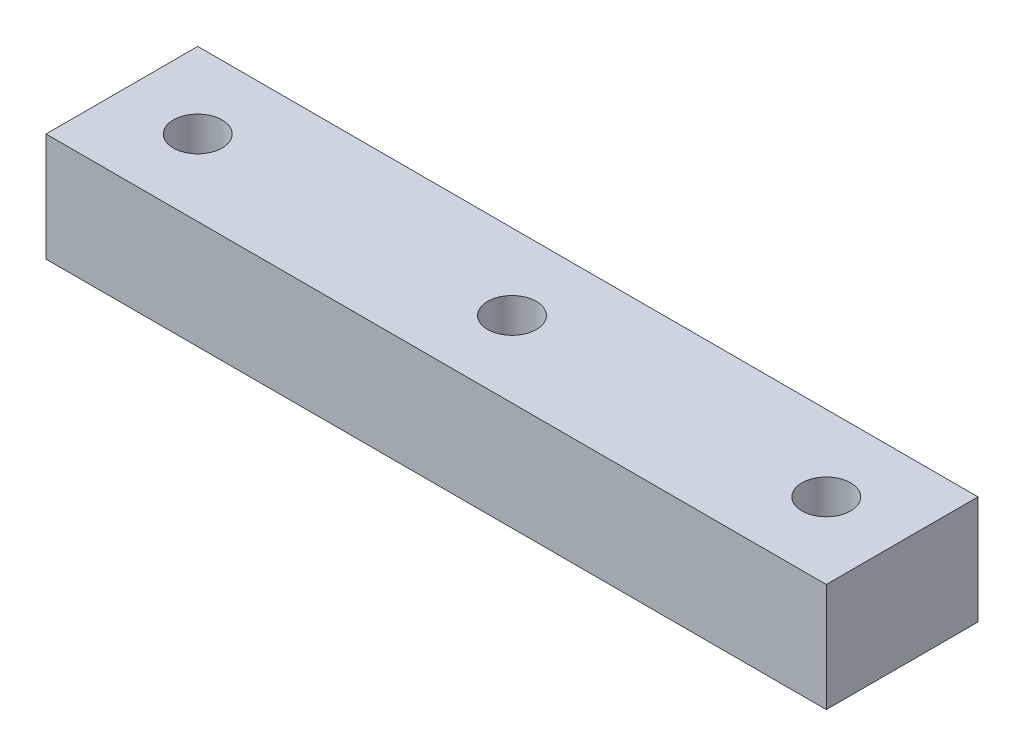
SolidWorks part; units mm, degrees
ref_plane "Front Plane" through (0, 0, 0) normal (0, 0, 1) x (1, 0, 0)
ref_plane "Top Plane" through (0, 0, 0) normal (0, 1, 0) x (1, 0, 0)
ref_plane "Right Plane" through (0, 0, 0) normal (1, 0, 0) x (0, 0, -1)
sketch "Sketch1" plane through (0, 0, 0) normal (0, 1, 0) x (1, 0, 0)
  line L1 (-36, -7) -> (36, -7)
  line L2 (-36, -7) -> (-36, 7)
  line L3 (-36, 7) -> (36, 7)
  line L4 (36, -7) -> (36, 7)
  line L5 (-36, -7) -> (36, 7) construction
  line L6 (-36, 7) -> (36, -7) construction
  circle A0 centre (0, 0) radius 2.25
  circle A1 centre (-29, 0) radius 2.25
  circle A2 centre (29, 0) radius 2.25
  point P0 (0, 0)
  dimension "D3" = 4.5
  dimension "D4" = 4.5
  dimension "D5" = 4.5
  dimension "D1" = 14
  dimension "D2" = 72
extrude "Boss-Extrude1" add sketch "Sketch1" along normal blind 10
